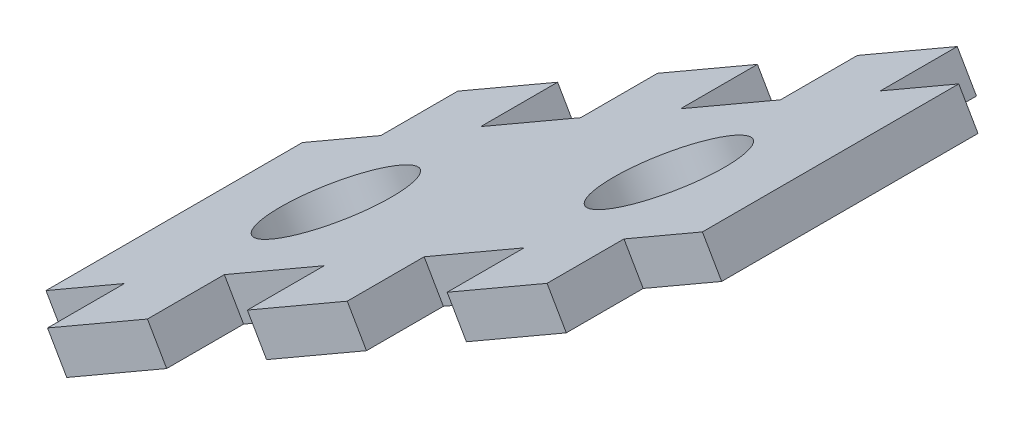
SolidWorks part; units mm, degrees
ref_plane "Plan de face" through (0, 0, 0) normal (0, 0, 1) x (1, 0, 0)
ref_plane "Plan de dessus" through (0, 0, 0) normal (0, 1, 0) x (1, 0, 0)
ref_plane "Plan de droite" through (0, 0, 0) normal (1, 0, 0) x (0, 0, -1)
sketch "Esquisse1" plane through (0, 0, 0) normal (0, 0, 1) x (1, 0, 0)
  line L0 (-90.9219, -229.1333) -> (-80.9219, -246.4538) construction
  line L1 (-80.9219, -246.4538) -> (21.5, -187.3205) construction
  line L2 (21.5, -187.3205) -> (11.5, -170) construction
  line L3 (11.5, -170) -> (11.5, 10) construction
  line L4 (-90.9219, -229.1333) -> (11.5, -170) construction
  line L5 (-82.4219, -243.8558) -> (20, -184.7224)
  line L6 (-82.4219, -243.8558) -> (-79.4219, -249.0519)
  line L7 (20, -184.7224) -> (23, -189.9186)
  line L8 (-79.4219, -249.0519) -> (23, -189.9186)
  line L9 (-82.4219, -243.8558) -> (23, -189.9186) construction
  line L10 (20, -184.7224) -> (-79.4219, -249.0519) construction
  point P10 (-29.711, -216.8872)
  point P12 (-29.711, -216.8872)
  dimension "D1" = 20
  dimension "D2" = 6
extrude "Boss.-Extru.1" add sketch "Esquisse1" along normal up to surface (40 mm away)
sketch "Esquisse3" plane through (0, 0, 0) normal (0, 0, -1) x (-1, 0, 0)
  line L0 (31.211, -214.2891) -> (28.211, -219.4853)
  line L1 (-20, -184.7224) -> (82.4219, -243.8558) construction
  line L2 (79.4219, -249.0519) -> (-23, -189.9186) construction
  line L3 (36.0052, -223.9853) -> (20.4167, -214.9853)
  line L4 (20.4167, -214.9853) -> (23.4167, -209.7891)
  line L5 (23.4167, -209.7891) -> (39.0052, -218.7891)
  line L6 (7.8283, -200.7891) -> (4.8283, -205.9853)
  line L7 (4.8283, -205.9853) -> (-10.7602, -196.9853)
  line L8 (-10.7602, -196.9853) -> (-7.7602, -191.7891)
  line L9 (-7.7602, -191.7891) -> (7.8283, -200.7891)
  line L10 (67.1821, -241.9853) -> (70.1821, -236.7891)
  line L11 (51.5937, -232.9853) -> (67.1821, -241.9853)
  line L12 (54.5937, -227.7891) -> (51.5937, -232.9853)
  line L13 (70.1821, -236.7891) -> (54.5937, -227.7891)
  line L14 (36.0052, -223.9853) -> (39.0052, -218.7891)
  line M10 (82.4219, -243.8558) -> (-20, -184.7224)
  line M12 (-23, -189.9186) -> (79.4219, -249.0519)
  dimension "D1" = 9
  dimension "D2" = 18
  dimension "D3" = 18
extrude "Boss.-Extru.2" add sketch "Esquisse3" along normal blind 12 and the other way blind 52 contours L8 L6 M12 M10 | L14 L0 M12 M10 | L4 L0 M12 M10 | L12 L10 M10 M12
sketch "Esquisse2" plane through (84.9872, -147.2021, 0) normal (-0.5, 0.866, 0) x (0.866, 0.5, 0)
  line L0 (-193.3074, -20) -> (-75.0407, -20) construction
  line L1 (-193.3074, -40) -> (-193.3074, 0) construction
  line L2 (-75.0407, -40) -> (-75.0407, 0) construction
  circle A0 centre (-164.174, -20) radius 10
  circle A1 centre (-104.174, -20) radius 10
  point P10 (-134.174, -20)
  dimension "D1" = 20
  dimension "D2" = 20
  dimension "D3" = 30
  dimension "D4" = 30
extrude "Enlèv. mat.-Extru.2" cut sketch "Esquisse2" against normal blind 12
equation "\"D2@Esquisse3\"=2*\"D1@Esquisse3\""
equation "\"D3@Esquisse3\"=\"D2@Esquisse3\""
